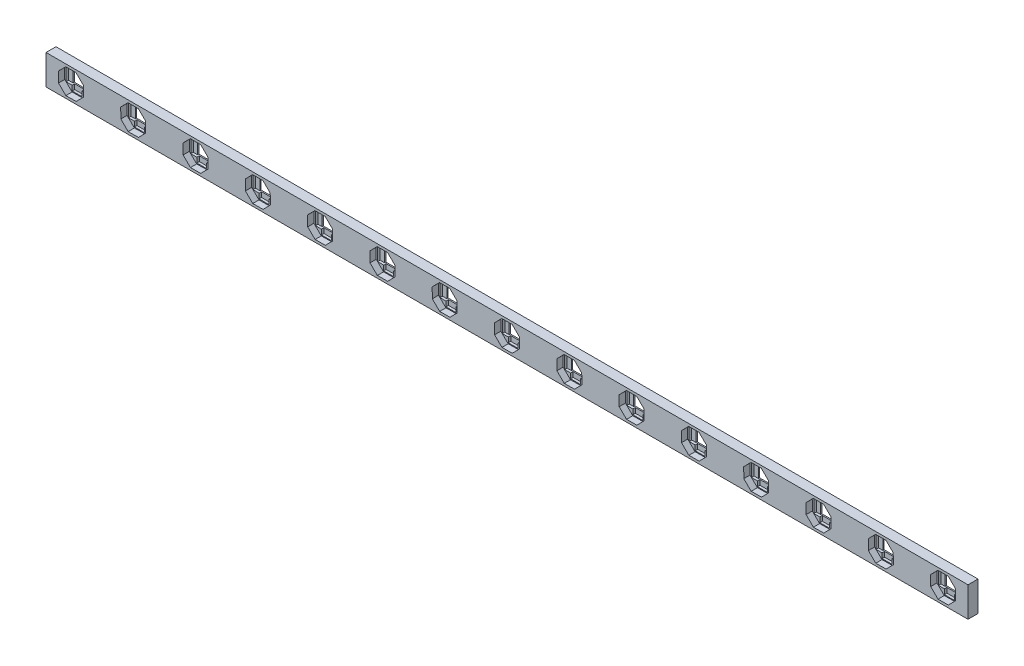
SolidWorks part; units mm, degrees
ref_plane "Front Plane" through (0, 0, 0) normal (0, 0, 1) x (1, 0, 0)
ref_plane "Top Plane" through (0, 0, 0) normal (0, 1, 0) x (1, 0, 0)
ref_plane "Right Plane" through (0, 0, 0) normal (1, 0, 0) x (0, 0, -1)
sketch "Sketch1" plane through (0, 0, 0) normal (0, 0, 1) x (1, 0, 0)
  line L1 (-379.6992, 7.2632) -> (-9.6992, 7.2632)
  line L2 (-379.6992, 7.2632) -> (-379.6992, -4.7368)
  line L3 (-379.6992, -4.7368) -> (-9.6992, -4.7368)
  line L4 (-9.6992, 7.2632) -> (-9.6992, -4.7368)
  dimension "D1" = 370
  dimension "D2" = 12
extrude "Boss-Extrude1" add sketch "Sketch1" along normal blind 4
sketch "Sketch3" plane through (0, 0, 4) normal (0, 0, 1) x (1, 0, 0)
  line L0 (-9.6992, -4.7368) -> (-9.6992, 7.2632) construction
  line L1 (-17.5892, -3.7205) -> (-14.6832, -0.7688)
  line L2 (-14.6832, -0.7688) -> (-14.7156, 3.3732)
  line L3 (-14.7156, 3.3732) -> (-17.6673, 6.2792)
  line L4 (-17.6673, 6.2792) -> (-21.8093, 6.2468)
  line L5 (-21.8093, 6.2468) -> (-24.7153, 3.2951)
  line L6 (-24.7153, 3.2951) -> (-24.6829, -0.8469)
  line L7 (-24.6829, -0.8469) -> (-21.7312, -3.7529)
  line L8 (-21.7312, -3.7529) -> (-17.5892, -3.7205)
  line L9 (-379.6992, -4.7368) -> (-9.6992, -4.7368) construction
  circle A0 centre (-19.6992, 1.2632) radius 5 construction
  dimension "D3" = 10
  dimension "D1" = 10
  dimension "D2" = 6
extrude "Cut-Extrude1" cut sketch "Sketch3" against normal blind 2.5
sketch "Sketch4" plane through (0, 0, 1.5) normal (0, 0, 1) x (1, 0, 0)
  line L1 (-22.3492, 3.9132) -> (-17.0492, 3.9132)
  line L2 (-22.3492, 3.9132) -> (-22.3492, -1.3868)
  line L3 (-22.3492, -1.3868) -> (-17.0492, -1.3868)
  line L4 (-17.0492, 3.9132) -> (-17.0492, -1.3868)
  line L13 (-9.6992, -4.7368) -> (-9.6992, 7.2632) construction
  line L14 (-379.6992, -4.7368) -> (-9.6992, -4.7368) construction
  dimension "D1" = 5.3
  dimension "D2" = 5.3
  dimension "D3" = 7.35
  dimension "D4" = 3.35
extrude "Cut-Extrude2" cut sketch "Sketch4" against normal through all
sketch "Sketch6" plane through (0, 0, 1.5) normal (0, 0, 1) x (1, 0, 0)
  line L0 (-22.3492, -1.3868) -> (-17.0492, -1.3868) construction
  line L1 (-21.6992, -1.3868) -> (-17.6992, -1.3868)
  line L2 (-21.6992, -1.3868) -> (-21.6992, -3.3868)
  line L3 (-21.6992, -3.3868) -> (-17.6992, -3.3868)
  line L4 (-17.6992, -1.3868) -> (-17.6992, -3.3868)
  line L7 (-9.6992, -4.7368) -> (-9.6992, 7.2632) construction
  line L8 (-379.6992, -4.7368) -> (-9.6992, -4.7368) construction
  dimension "D1" = 4
  dimension "D2" = 2
  dimension "D3" = 8
  dimension "D4" = 1.35
extrude "Cut-Extrude3" cut sketch "Sketch6" against normal blind 1
sketch "Sketch7" plane through (0, 0, 1.5) normal (0, 0, 1) x (1, 0, 0)
  line L0 (-17.0492, 3.9132) -> (-22.3492, 3.9132) construction
  line L1 (-21.6992, 3.9132) -> (-17.6992, 3.9132)
  line L2 (-21.6992, 3.9132) -> (-21.6992, 5.9132)
  line L3 (-21.6992, 5.9132) -> (-17.6992, 5.9132)
  line L4 (-17.6992, 3.9132) -> (-17.6992, 5.9132)
  line L6 (-9.6992, -4.7368) -> (-9.6992, 7.2632) construction
  dimension "D1" = 2
  dimension "D2" = 4
  dimension "D3" = 8
extrude "Cut-Extrude4" cut sketch "Sketch7" against normal blind 1
sketch "Sketch10" plane through (0, 0, 1.5) normal (0, 0, 1) x (1, 0, 0)
  line L1 (-17.0492, 3.9132) -> (-15.2992, 3.9132)
  line L2 (-17.0492, 3.9132) -> (-17.0492, -1.4203)
  line L3 (-17.0492, -1.4203) -> (-15.2992, -1.4203)
  line L4 (-15.2992, 3.9132) -> (-15.2992, -1.4203)
  line L5 (-22.3492, -1.3868) -> (-24.0992, -1.3868)
  line L6 (-22.3492, -1.3868) -> (-22.3492, 3.9132)
  line L7 (-22.3492, 3.9132) -> (-24.0992, 3.9132)
  line L8 (-24.0992, -1.3868) -> (-24.0992, 3.9132)
  dimension "D1" = 1.75
  dimension "D2" = 1.75
extrude "Cut-Extrude7" cut sketch "Sketch10" against normal blind 1
pattern_linear "LPattern1" count 15 spacing 25 along (-1, 0, 0) of "Cut-Extrude1", "Cut-Extrude2", "Cut-Extrude3", "Cut-Extrude4", "Cut-Extrude7"
